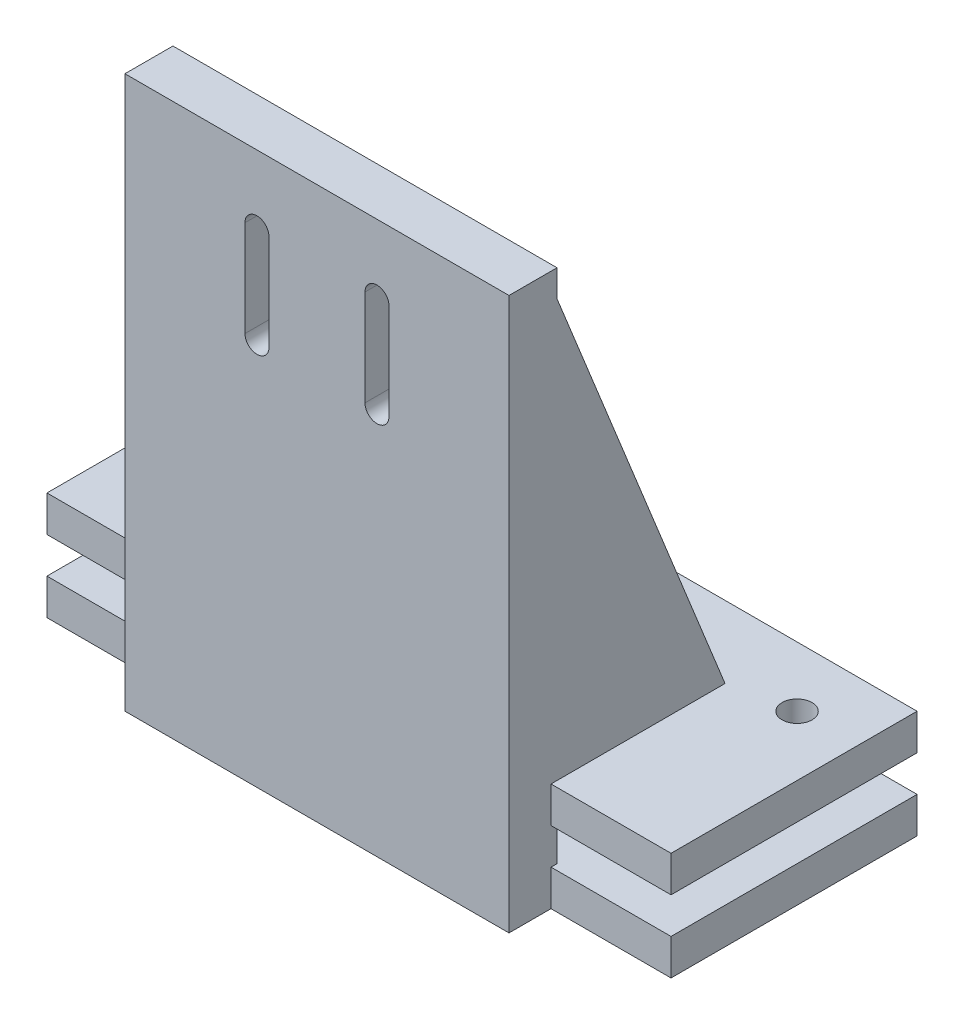
SolidWorks part; units mm, degrees
ref_plane "前视基准面" through (0, 0, 0) normal (0, 0, 1) x (1, 0, 0)
ref_plane "上视基准面" through (0, 0, 0) normal (0, 1, 0) x (1, 0, 0)
ref_plane "右视基准面" through (0, 0, 0) normal (1, 0, 0) x (0, 0, -1)
sketch "草图1" plane through (0, 0, 0) normal (0, 0, 1) x (1, 0, 0)
  line L1 (-32, -11.5) -> (32, -11.5)
  line L2 (-32, -11.5) -> (-32, 80.5)
  line L3 (-32, 80.5) -> (32, 80.5)
  line L4 (32, -11.5) -> (32, 80.5)
  line L5 (-32, -11.5) -> (32, 80.5) construction
  line L6 (-32, 80.5) -> (32, -11.5) construction
  point P0 (0, 34.5)
  dimension "D1" = 32
  dimension "D2" = 34.5
  dimension "D3" = 80.5
extrude "连接滑台背面_固定安装板" add sketch "草图1" along normal blind 8
sketch "草图2" plane through (0, 0, 0) normal (0, 0, 1) x (1, 0, 0)
  line L1 (-52, -11.5) -> (52, -11.5)
  line L2 (-52, -11.5) -> (-52, -5.5)
  line L3 (-52, -5.5) -> (52, -5.5)
  line L4 (52, -11.5) -> (52, -5.5)
  line L5 (-52, -11.5) -> (52, -5.5) construction
  line L6 (-52, -5.5) -> (52, -11.5) construction
  point P0 (0, -8.5)
  dimension "D1" = 52
  dimension "D2" = 5.5
  dimension "D3" = 8.5
extrude "下包边板_C槽净高6" add sketch "草图2" along normal blind 41 from offset 40
sketch "草图3" plane through (0, 0, 0) normal (0, 0, 1) x (1, 0, 0)
  line L1 (-52, 0.5) -> (52, 0.5)
  line L2 (-52, 0.5) -> (-52, 6.5)
  line L3 (-52, 6.5) -> (52, 6.5)
  line L4 (52, 0.5) -> (52, 6.5)
  line L5 (-52, 0.5) -> (52, 6.5) construction
  line L6 (-52, 6.5) -> (52, 0.5) construction
  point P0 (0, 3.5)
  dimension "D1" = 52
  dimension "D2" = 0.5
  dimension "D3" = 3.5
extrude "上包边板_C槽净高6" add sketch "草图3" along normal blind 41 from offset 40
sketch "草图4" plane through (0, 0, 0) normal (1, 0, 0) x (0, 0, -1)
  line L0 (28, 6.5) -> (-1, 6.5)
  line L1 (-1, 6.5) -> (-1, 78.5)
  line L2 (-1, 78.5) -> (28, 6.5)
  dimension "D1" = 28
  dimension "D2" = 1
  dimension "D3" = 6.5
  dimension "D4" = 78.5
extrude "侧边三角加强筋" add sketch "草图4" along normal blind 6 from offset 32
sketch "草图5" plane through (0, 0, 0) normal (1, 0, 0) x (0, 0, -1)
  line L0 (28, 6.5) -> (-1, 6.5)
  line L1 (-1, 6.5) -> (-1, 78.5)
  line L2 (-1, 78.5) -> (28, 6.5)
  dimension "D1" = 28
  dimension "D2" = 1
  dimension "D3" = 6.5
  dimension "D4" = 78.5
extrude "凸台-拉伸5" add sketch "草图5" along normal blind 6 from offset 26
sketch "草图6" plane through (0, 0, 0) normal (0, 0, 1) x (1, 0, 0)
  line L0 (-8, 53) -> (-8, 69)
  line L1 (-12, 69) -> (-12, 53)
  line L2 (12, 53) -> (12, 69)
  line L3 (8, 69) -> (8, 53)
  arc A0 (-8, 69) -> (-12, 69) centre (-10, 69) ccw
  arc A1 (-12, 53) -> (-8, 53) centre (-10, 53) ccw
  arc A2 (12, 69) -> (8, 69) centre (10, 69) ccw
  arc A3 (8, 53) -> (12, 53) centre (10, 53) ccw
  dimension "D1" = 2
  dimension "D2" = 10
  dimension "D3" = 10
  dimension "D4" = 53
  dimension "D5" = 69
extrude "上下可调槽_中心行程正负8" cut sketch "草图6" along normal blind 8
sketch "草图7" plane through (0, 0, 0) normal (0, 1, 0) x (1, 0, 0)
  circle A0 centre (-42, 30) radius 2.5
  circle A1 centre (42, 30) radius 2.5
  dimension "D1" = 5
  dimension "D2" = 42
  dimension "D3" = 42
  dimension "D4" = 30
extrude "两翼共用车板孔_不直接攻塑料牙" cut sketch "草图7" along normal blind 18 from offset 11.5
